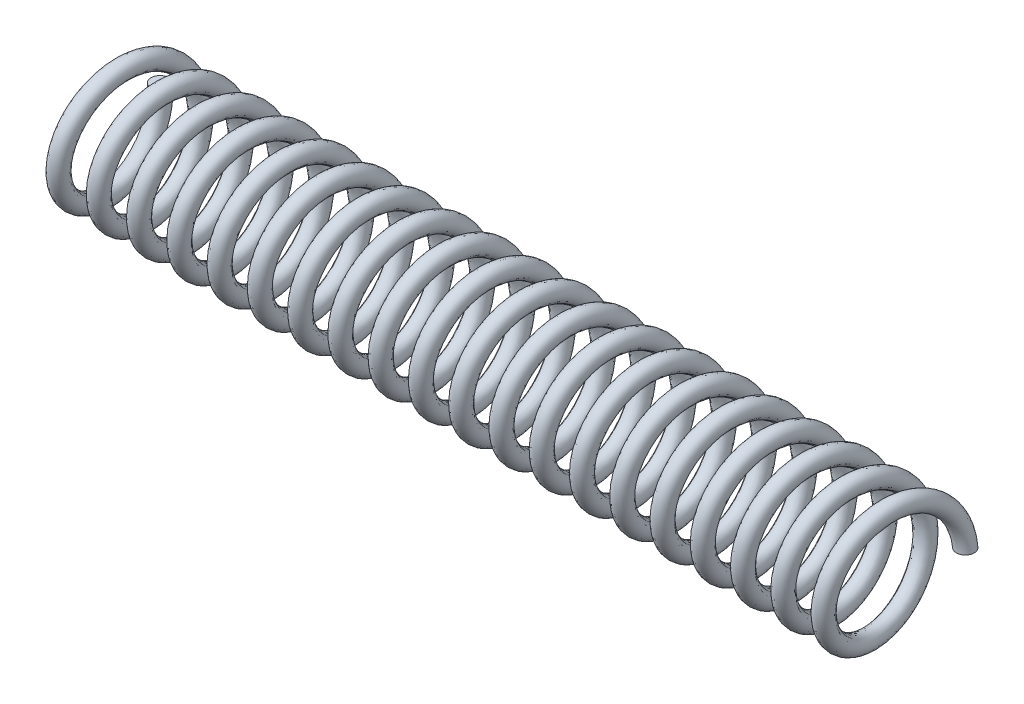
SolidWorks part; units mm, degrees
material "Bronce de aluminio"
ref_plane "Alzado" through (0, 0, 0) normal (0, 0, 1) x (1, 0, 0)
ref_plane "Planta" through (0, 0, 0) normal (0, 1, 0) x (1, 0, 0)
ref_plane "Vista lateral" through (0, 0, 0) normal (1, 0, 0) x (0, 0, -1)
sketch "Croquis1" plane through (0, 0, 0) normal (1, 0, 0) x (0, 0, -1)
  circle A0 centre (0, 0) radius 10
  dimension "D1" = 20
curve "Hélice/Espiral1" pitch 2.25 height 45 turns 20
sketch "Croquis2" plane through (0, 0, 0) normal (0, 1, 0) x (1, 0, 0)
  circle A0 centre (40.0612, 3.3867) radius 0.5
  spline S0 degree 3 poles (0, 10) (0.0466, 10) (0.1408, 9.4793) (0.2812, 7.2552) (0.4219, 3.9265) (0.5625, 0) (0.7031, -3.9265) (0.8437, -7.2552) (0.9844, -9.4793) (1.125, -10.2603) (1.2656, -9.4793) (1.4062, -7.2552) (1.5938, -2.8169) (1.7813, 2.8169) (1.9687, 7.2552) (2.1094, 9.4793) (2.25, 10.2603) (2.3906, 9.4793) (2.5312, 7.2552) (2.7188, 2.8169) (2.9063, -2.8169) (3.0938, -7.2552) (3.2344, -9.4793) (3.375, -10.2603) (3.5156, -9.4793) (3.6562, -7.2552) (3.8438, -2.8169) (4.0313, 2.8169) (4.2188, 7.2552) (4.3594, 9.4793) (4.5, 10.2603) (4.6406, 9.4793) (4.7813, 7.2552) (4.9688, 2.8169) (5.1562, -2.8169) (5.3438, -7.2552) (5.4844, -9.4793) (5.625, -10.2603) (5.7656, -9.4793) (5.9063, -7.2552) (6.0938, -2.8169) (6.2813, 2.8169) (6.4688, 7.2552) (6.6094, 9.4793) (6.75, 10.2603) (6.8906, 9.4793) (7.0313, 7.2552) (7.2188, 2.8169) (7.4063, -2.8169) (7.5938, -7.2552) (7.7344, -9.4793) (7.875, -10.2603) (8.0156, -9.4793) (8.1563, -7.2552) (8.3438, -2.8169) (8.5313, 2.8169) (8.7188, 7.2552) (8.8594, 9.4793) (9, 10.2603) (9.1406, 9.4793) (9.2813, 7.2552) (9.4688, 2.8169) (9.6563, -2.8169) (9.8438, -7.2552) (9.9844, -9.4793) (10.125, -10.2603) (10.2656, -9.4793) (10.4063, -7.2552) (10.5938, -2.8169) (10.7813, 2.8169) (10.9688, 7.2552) (11.1094, 9.4793) (11.25, 10.2603) (11.3906, 9.4793) (11.5313, 7.2552) (11.7187, 2.8169) (11.9063, -2.8169) (12.0938, -7.2552) (12.2344, -9.4793) (12.375, -10.2603) (12.5156, -9.4793) (12.6563, -7.2552) (12.8438, -2.8169) (13.0313, 2.8169) (13.2188, 7.2552) (13.3594, 9.4793) (13.5, 10.2603) (13.6406, 9.4793) (13.7813, 7.2552) (13.9688, 2.8169) (14.1563, -2.8169) (14.3438, -7.2552) (14.4844, -9.4793) (14.625, -10.2603) (14.7656, -9.4793) (14.9063, -7.2552) (15.0938, -2.8169) (15.2813, 2.8169) (15.4688, 7.2552) (15.6094, 9.4793) (15.75, 10.2603) (15.8906, 9.4793) (16.0313, 7.2552) (16.2187, 2.8169) (16.4062, -2.8169) (16.5938, -7.2552) (16.7344, -9.4793) (16.875, -10.2603) (17.0156, -9.4793) (17.1562, -7.2552) (17.3437, -2.8169) (17.5312, 2.8169) (17.7187, 7.2552) (17.8594, 9.4793) (18, 10.2603) (18.1406, 9.4793) (18.2812, 7.2552) (18.4687, 2.8169) (18.6562, -2.8169) (18.8437, -7.2552) (18.9844, -9.4793) (19.125, -10.2603) (19.2656, -9.4793) (19.4062, -7.2552) (19.5937, -2.8169) (19.7812, 2.8169) (19.9687, 7.2552) (20.1094, 9.4793) (20.25, 10.2603) (20.3906, 9.4793) (20.5312, 7.2552) (20.7187, 2.8169) (20.9062, -2.8169) (21.0937, -7.2552) (21.2344, -9.4793) (21.375, -10.2603) (21.5156, -9.4793) (21.6562, -7.2552) (21.8437, -2.8169) (22.0312, 2.8169) (22.2187, 7.2552) (22.3594, 9.4793) (22.5, 10.2603) (22.6406, 9.4793) (22.7812, 7.2552) (22.9687, 2.8169) (23.1562, -2.8169) (23.3437, -7.2552) (23.4844, -9.4793) (23.625, -10.2603) (23.7656, -9.4793) (23.9062, -7.2552) (24.0937, -2.8169) (24.2812, 2.8169) (24.4687, 7.2552) (24.6094, 9.4793) (24.75, 10.2603) (24.8906, 9.4793) (25.0312, 7.2552) (25.2187, 2.8169) (25.4062, -2.8169) (25.5937, -7.2552) (25.7344, -9.4793) (25.875, -10.2603) (26.0156, -9.4793) (26.1562, -7.2552) (26.3437, -2.8169) (26.5312, 2.8169) (26.7187, 7.2552) (26.8594, 9.4793) (27, 10.2603) (27.1406, 9.4793) (27.2812, 7.2552) (27.4687, 2.8169) (27.6562, -2.8169) (27.8437, -7.2552) (27.9844, -9.4793) (28.125, -10.2603) (28.2656, -9.4793) (28.4062, -7.2552) (28.5937, -2.8169) (28.7812, 2.8169) (28.9687, 7.2552) (29.1094, 9.4793) (29.25, 10.2603) (29.3906, 9.4793) (29.5312, 7.2552) (29.7187, 2.8169) (29.9062, -2.8169) (30.0937, -7.2552) (30.2344, -9.4793) (30.375, -10.2603) (30.5156, -9.4793) (30.6562, -7.2552) (30.8437, -2.8169) (31.0312, 2.8169) (31.2187, 7.2552) (31.3594, 9.4793) (31.5, 10.2603) (31.6406, 9.4793) (31.7812, 7.2552) (31.9687, 2.8169) (32.1562, -2.8169) (32.3437, -7.2552) (32.4844, -9.4793) (32.625, -10.2603) (32.7656, -9.4793) (32.9062, -7.2552) (33.0937, -2.8169) (33.2812, 2.8169) (33.4687, 7.2552) (33.6094, 9.4793) (33.75, 10.2603) (33.8906, 9.4793) (34.0312, 7.2552) (34.2187, 2.8169) (34.4062, -2.8169) (34.5937, -7.2552) (34.7344, -9.4793) (34.875, -10.2603) (35.0156, -9.4793) (35.1562, -7.2552) (35.3437, -2.8169) (35.5312, 2.8169) (35.7187, 7.2552) (35.8594, 9.4793) (36, 10.2603) (36.1406, 9.4793) (36.2812, 7.2552) (36.4687, 2.8169) (36.6562, -2.8169) (36.8437, -7.2552) (36.9844, -9.4793) (37.125, -10.2603) (37.2656, -9.4793) (37.4062, -7.2552) (37.5937, -2.8169) (37.7812, 2.8169) (37.9687, 7.2552) (38.1094, 9.4793) (38.25, 10.2603) (38.3906, 9.4793) (38.5312, 7.2552) (38.7187, 2.8169) (38.9062, -2.8169) (39.0937, -7.2552) (39.2344, -9.4793) (39.375, -10.2603) (39.5156, -9.4793) (39.6562, -7.2552) (39.8437, -2.8169) (40.0312, 2.8169) (40.2187, 7.2552) (40.3594, 9.4793) (40.5, 10.2603) (40.6406, 9.4793) (40.7812, 7.2552) (40.9687, 2.8169) (41.1562, -2.8169) (41.3437, -7.2552) (41.4844, -9.4793) (41.625, -10.2603) (41.7656, -9.4793) (41.9062, -7.2552) (42.0937, -2.8169) (42.2812, 2.8169) (42.4687, 7.2552) (42.6094, 9.4793) (42.75, 10.2603) (42.8906, 9.4793) (43.0313, 7.2552) (43.2187, 2.8169) (43.4062, -2.8169) (43.5938, -7.2552) (43.7344, -9.4793) (43.875, -10.2603) (44.0156, -9.4793) (44.1563, -7.2552) (44.2969, -3.9265) (44.4375, 0) (44.5781, 3.9265) (44.7188, 7.2552) (44.8592, 9.4793) (44.9534, 10) (45, 10) knots 0 0 0 0 0.003125 0.00625 0.009375 0.0125 0.015625 0.01875 0.021875 0.025 0.028125 0.03125 0.034375 0.040625 0.04375 0.046875 0.05 0.053125 0.05625 0.059375 0.065625 0.06875 0.071875 0.075 0.078125 0.08125 0.084375 0.090625 0.09375 0.096875 0.1 0.103125 0.10625 0.109375 0.115625 0.11875 0.121875 0.125 0.128125 0.13125 0.134375 0.140625 0.14375 0.146875 0.15 0.153125 0.15625 0.159375 0.165625 0.16875 0.171875 0.175 0.178125 0.18125 0.184375 0.190625 0.19375 0.196875 0.2 0.203125 0.20625 0.209375 0.215625 0.21875 0.221875 0.225 0.228125 0.23125 0.234375 0.240625 0.24375 0.246875 0.25 0.253125 0.25625 0.259375 0.265625 0.26875 0.271875 0.275 0.278125 0.28125 0.284375 0.290625 0.29375 0.296875 0.3 0.303125 0.30625 0.309375 0.315625 0.31875 0.321875 0.325 0.328125 0.33125 0.334375 0.340625 0.34375 0.346875 0.35 0.353125 0.35625 0.359375 0.365625 0.36875 0.371875 0.375 0.378125 0.38125 0.384375 0.390625 0.39375 0.396875 0.4 0.403125 0.40625 0.409375 0.415625 0.41875 0.421875 0.425 0.428125 0.43125 0.434375 0.440625 0.44375 0.446875 0.45 0.453125 0.45625 0.459375 0.465625 0.46875 0.471875 0.475 0.478125 0.48125 0.484375 0.490625 0.49375 0.496875 0.5 0.503125 0.50625 0.509375 0.515625 0.51875 0.521875 0.525 0.528125 0.53125 0.534375 0.540625 0.54375 0.546875 0.55 0.553125 0.55625 0.559375 0.565625 0.56875 0.571875 0.575 0.578125 0.58125 0.584375 0.590625 0.59375 0.596875 0.6 0.603125 0.60625 0.609375 0.615625 0.61875 0.621875 0.625 0.628125 0.63125 0.634375 0.640625 0.64375 0.646875 0.65 0.653125 0.65625 0.659375 0.665625 0.66875 0.671875 0.675 0.678125 0.68125 0.684375 0.690625 0.69375 0.696875 0.7 0.703125 0.70625 0.709375 0.715625 0.71875 0.721875 0.725 0.728125 0.73125 0.734375 0.740625 0.74375 0.746875 0.75 0.753125 0.75625 0.759375 0.765625 0.76875 0.771875 0.775 0.778125 0.78125 0.784375 0.790625 0.79375 0.796875 0.8 0.803125 0.80625 0.809375 0.815625 0.81875 0.821875 0.825 0.828125 0.83125 0.834375 0.840625 0.84375 0.846875 0.85 0.853125 0.85625 0.859375 0.865625 0.86875 0.871875 0.875 0.878125 0.88125 0.884375 0.890625 0.89375 0.896875 0.9 0.903125 0.90625 0.909375 0.915625 0.91875 0.921875 0.925 0.928125 0.93125 0.934375 0.940625 0.94375 0.946875 0.95 0.953125 0.95625 0.959375 0.965625 0.96875 0.971875 0.975 0.978125 0.98125 0.984375 0.9875 0.990625 0.99375 0.996875 1 1 1 1 construction
  dimension "D1" = 1
sweep "Barrer1" add profiles "Croquis2" path "Hélice/Espiral1"
